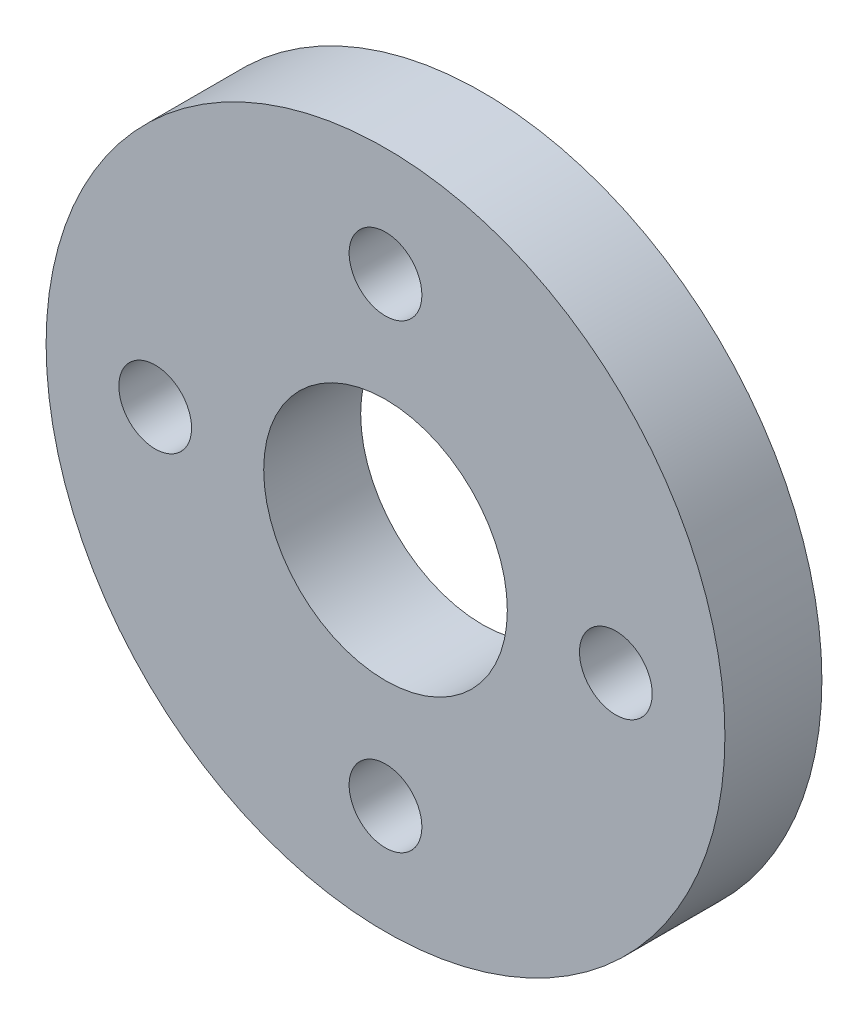
SolidWorks part; units mm, degrees
ref_plane "前视基准面" through (0, 0, 0) normal (0, 0, 1) x (1, 0, 0)
ref_plane "上视基准面" through (0, 0, 0) normal (0, 1, 0) x (1, 0, 0)
ref_plane "右视基准面" through (0, 0, 0) normal (1, 0, 0) x (0, 0, -1)
sketch "草图1" plane through (0, 0, 0) normal (0, 0, 1) x (1, 0, 0)
  circle A0 centre (0, 0) radius 14
  circle A1 centre (0, 0) radius 5.025
  circle A2 centre (0, -9.5) radius 1.5
  circle A3 centre (-9.5, 0) radius 1.5
  circle A4 centre (0, 9.5) radius 1.5
  circle A5 centre (9.5, 0) radius 1.5
  dimension "D1" = 28
  dimension "D2" = 10.05
  dimension "D3" = 9.5
  dimension "D4" = 4
  dimension "D5" = 3
extrude "凸台-拉伸1" add sketch "草图1" along normal blind 4
